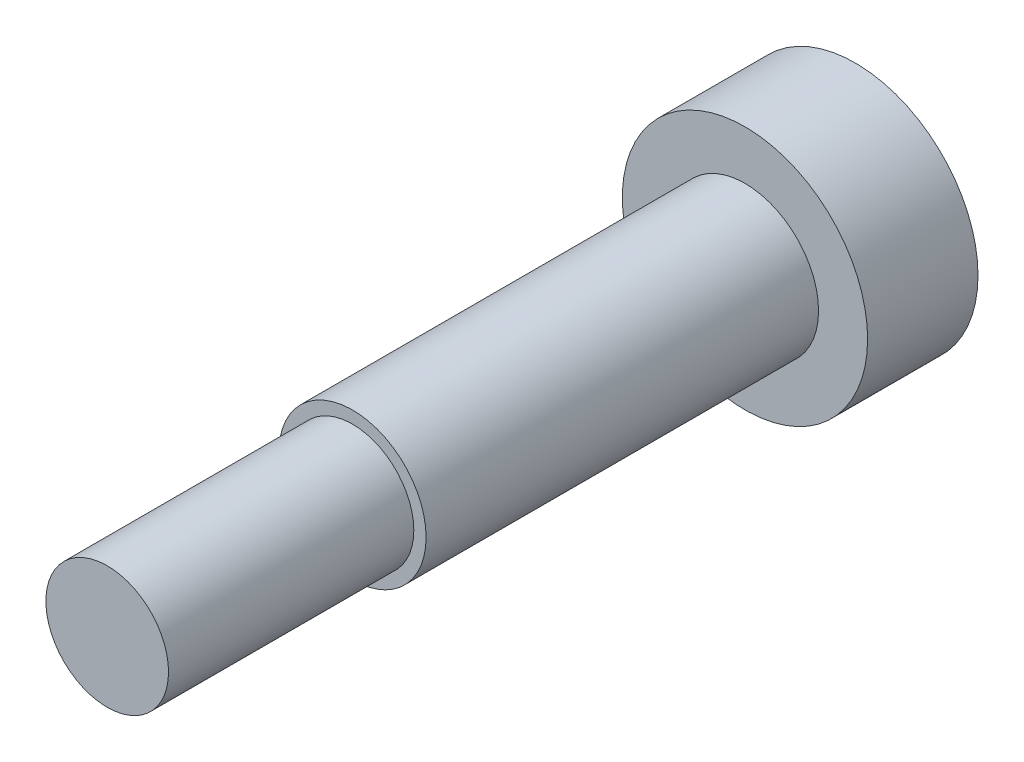
SolidWorks part; units mm, degrees
ref_plane "前视基准面" through (0, 0, 0) normal (0, 0, 1) x (1, 0, 0)
ref_plane "上视基准面" through (0, 0, 0) normal (0, 1, 0) x (1, 0, 0)
ref_plane "右视基准面" through (0, 0, 0) normal (1, 0, 0) x (0, 0, -1)
sketch "草图1" plane through (0, 0, 0) normal (0, 0, 1) x (1, 0, 0)
  circle A0 centre (0, 0) radius 5
extrude "凸台-拉伸1" add sketch "草图1" along normal blind 4.5
sketch "草图2" plane through (0, 0, 0) normal (0, 0, -1) x (-1, 0, 0)
  line L1 (1.5, -0.866) -> (1.5, 0.866)
  line L2 (1.5, 0.866) -> (0, 1.7321)
  line L3 (0, 1.7321) -> (-1.5, 0.866)
  line L4 (-1.5, 0.866) -> (-1.5, -0.866)
  line L5 (-1.5, -0.866) -> (0, -1.7321)
  line L6 (0, -1.7321) -> (1.5, -0.866)
  circle A0 centre (0, 0) radius 1.5 construction
  dimension "D1" = 3
extrude "切除-拉伸1" cut sketch "草图2" against normal blind 2
sketch "草图3" plane through (0, 0, 4.5) normal (0, 0, 1) x (1, 0, 0)
  circle A0 centre (0, 0) radius 3
extrude "凸台-拉伸2" add sketch "草图3" along normal blind 16
sketch "草图4" plane through (0, 0, 20.5) normal (0, 0, 1) x (1, 0, 0)
  circle A0 centre (0, 0) radius 2.5
extrude "凸台-拉伸3" add sketch "草图4" along normal blind 10
